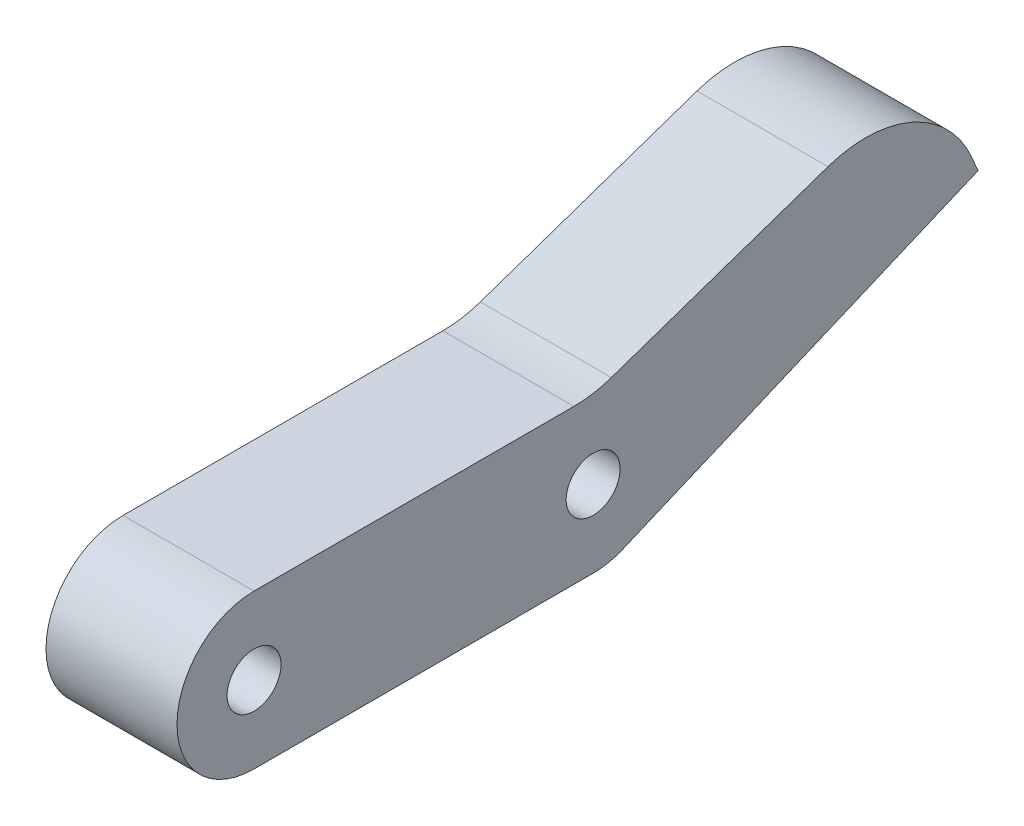
SolidWorks part; units mm, degrees
material "PVC 0.007 Plasticized"
ref_plane "Front Plane" through (0, 0, 0) normal (0, 0, 1) x (1, 0, 0)
ref_plane "Top Plane" through (0, 0, 0) normal (0, 1, 0) x (1, 0, 0)
ref_plane "Right Plane" through (0, 0, 0) normal (1, 0, 0) x (0, 0, -1)
sketch "Sketch1" plane through (0, 0, 0) normal (1, 0, 0) x (0, 0, -1)
  line L1 (0, 0) -> (27, 0)
  line L2 (0, 0) -> (0, 10)
  line L3 (0, 10) -> (27, 10)
  circle A0 centre (5, 5) radius 1.75
  circle A1 centre (5, 5) radius 5
  circle A2 centre (27, 5) radius 5
  circle A3 centre (27, 5) radius 1.75
  dimension "D7" = 3.5
  dimension "D11" = 10
  dimension "D2" = 3.5
  dimension "D1" = 10
  dimension "D8" = 5
  dimension "D9" = 5
  dimension "D10" = 22
extrude "Boss-Extrude1" add sketch "Sketch1" along normal blind 8.5 contours A1 A0 | A2 L3 A1 L1 | A2 A3 | L2 A1 | L1 A1
sketch "Sketch2" plane through (8.5, 0, 0) normal (1, 0, 0) x (0, 0, -1)
  line L1 (27, 10) -> (48.8579, 17.4993)
  line L3 (5, 0) -> (27, 0) construction
  line L6 (5, 10) -> (27, 10) construction
  line L14 (5, 10) -> (27, 10)
  line L20 (28.9472, 0.3948) -> (51.9735, 10.1309)
  line L22 (51.9735, 10.1309) -> (48.8579, 17.4993)
  arc A3 (27, 0) -> (27, 10) centre (27, 5) ccw construction
  arc A4 (27, 0) -> (27, 10) centre (27, 5) ccw
  point P2 (27, 5)
  dimension "D1" = 25
  dimension "D2" = 202.92
  dimension "D3" = 8
extrude "Boss-Extrude2" add sketch "Sketch2" against normal up to surface (8.5 mm away) up to face at (0, 5, -16)
fillet "Fillet1" radius 7.5 2 edges at (4.25, 17.4993, -48.8579) (4.25, 10, -27)
